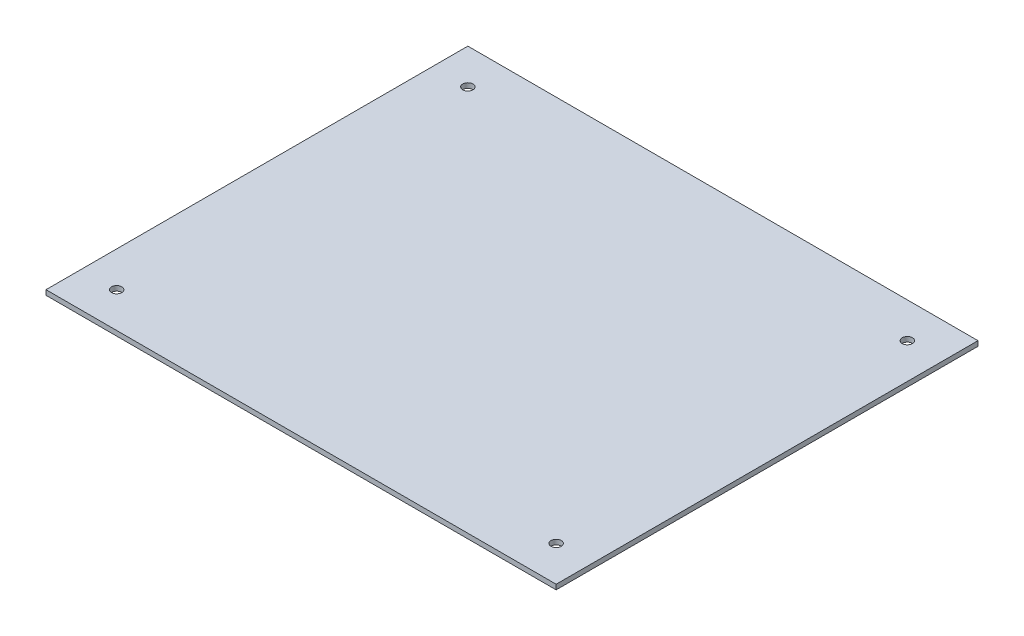
SolidWorks part; units mm, degrees
ref_plane "Front Plane" through (0, 0, 0) normal (0, 0, 1) x (1, 0, 0)
ref_plane "Top Plane" through (0, 0, 0) normal (0, 1, 0) x (1, 0, 0)
ref_plane "Right Plane" through (0, 0, 0) normal (1, 0, 0) x (0, 0, -1)
sketch "Sketch2" plane through (0, 0, 0) normal (0, 1, 0) x (1, 0, 0)
  line L1 (-165.1, 136.525) -> (165.1, 136.525)
  line L2 (-165.1, 136.525) -> (-165.1, -136.525)
  line L3 (-165.1, -136.525) -> (165.1, -136.525)
  line L4 (165.1, 136.525) -> (165.1, -136.525)
  line L5 (-165.1, 136.525) -> (165.1, -136.525) construction
  line L6 (-165.1, -136.525) -> (165.1, 136.525) construction
  point P0 (0, 0)
  dimension "D1" = 330.2
  dimension "D2" = 273.05
extrude "Boss-Extrude1" add sketch "Sketch2" along normal blind 3.175
sketch "Sketch3" plane through (0, 3.175, 0) normal (0, 1, 0) x (1, 0, 0)
  line L0 (-165.1, 136.525) -> (-165.1, -136.525) construction
  line L1 (-165.1, -136.525) -> (165.1, -136.525) construction
  line L2 (165.1, 136.525) -> (-165.1, 136.525) construction
  line L3 (165.1, -136.525) -> (165.1, 136.525) construction
  circle A0 centre (-142.24, -113.665) radius 3.302
  circle A1 centre (-142.24, 113.665) radius 3.302
  circle A4 centre (142.24, -113.665) radius 3.302
  circle A5 centre (142.24, 113.665) radius 3.302
  dimension "D9" = 6.604
  dimension "D1" = 22.86
  dimension "D2" = 22.86
  dimension "D3" = 22.86
  dimension "D4" = 22.86
  dimension "D5" = 22.86
  dimension "D6" = 22.86
  dimension "D7" = 22.86
  dimension "D8" = 22.86
extrude "Cut-Extrude1" cut sketch "Sketch3" against normal through all
